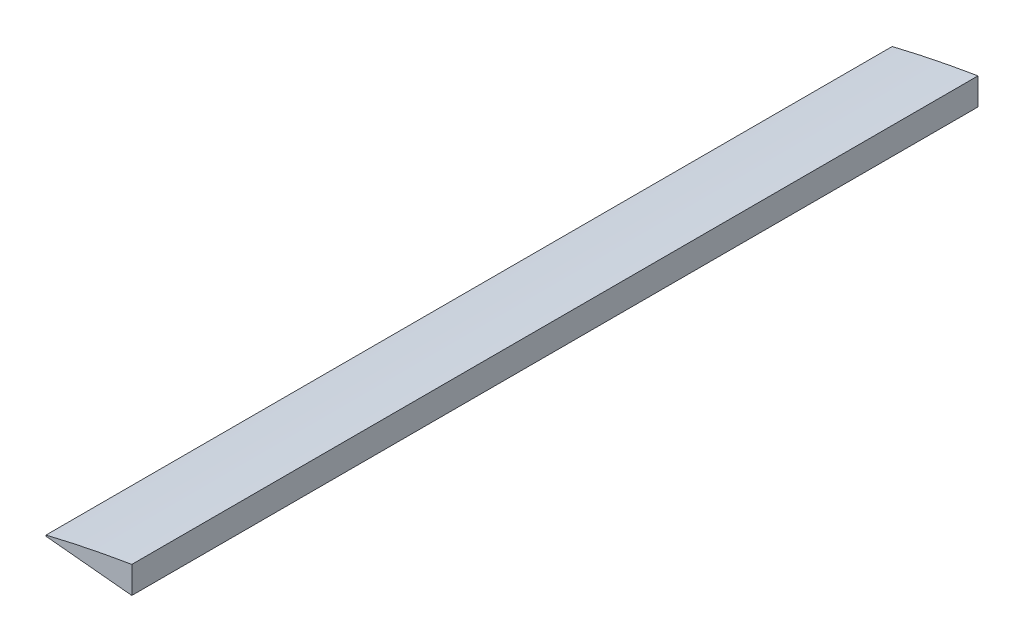
SolidWorks part; units mm, degrees
ref_plane "Front Plane" through (0, 0, 0) normal (0, 0, 1) x (1, 0, 0)
ref_plane "Top Plane" through (0, 0, 0) normal (0, 1, 0) x (1, 0, 0)
ref_plane "Right Plane" through (0, 0, 0) normal (1, 0, 0) x (0, 0, -1)
sketch "Sketch1" plane through (0, 0, 0) normal (0, 0, 1) x (1, 0, 0)
  line L0 (-176.6195, 13.0231) -> (-176.6195, -6.4544)
  line L1 (-238.675, 0.3812) -> (-238.675, -0.3751)
  spline S0 degree 3 poles (-176.6195, 13.0231) (-178.4319, 12.7225) (-182.8419, 11.9911) (-189.6921, 10.7708) (-197.0149, 9.4107) (-203.8537, 8.0796) (-210.1682, 6.8004) (-215.9209, 5.5913) (-221.0778, 4.4715) (-225.609, 3.4587) (-229.488, 2.5698) (-232.6924, 1.8199) (-235.2039, 1.2222) (-237.0081, 0.7872) (-238.0864, 0.525) (-238.5621, 0.4088) (-238.675, 0.3812) knots 0 0 0 0 0.087007 0.211705 0.329527 0.439741 0.541661 0.634652 0.718135 0.791585 0.85454 0.906603 0.947445 0.976805 0.994497 1 1 1 1
  spline S1 degree 3 poles (-176.6195, -6.4544) (-178.1888, -6.3121) (-182.3599, -5.934) (-188.9904, -5.3179) (-196.3547, -4.6242) (-203.2487, -3.9636) (-209.6287, -3.3428) (-215.4538, -2.7672) (-220.6864, -2.2426) (-225.2928, -1.7737) (-229.243, -1.3675) (-232.5108, -1.0239) (-235.0757, -0.761) (-236.9188, -0.5487) (-238.0316, -0.4591) (-238.5336, -0.3746) (-238.6667, -0.3751) (-238.675, -0.3751) knots 0 0 0 0 0.075811 0.201508 0.320388 0.431695 0.534719 0.628797 0.713321 0.78774 0.851567 0.90438 0.945827 0.975633 0.993597 0.999599 1 1 1 1
extrude "Boss-Extrude1" add sketch "Sketch1" against normal blind 612
